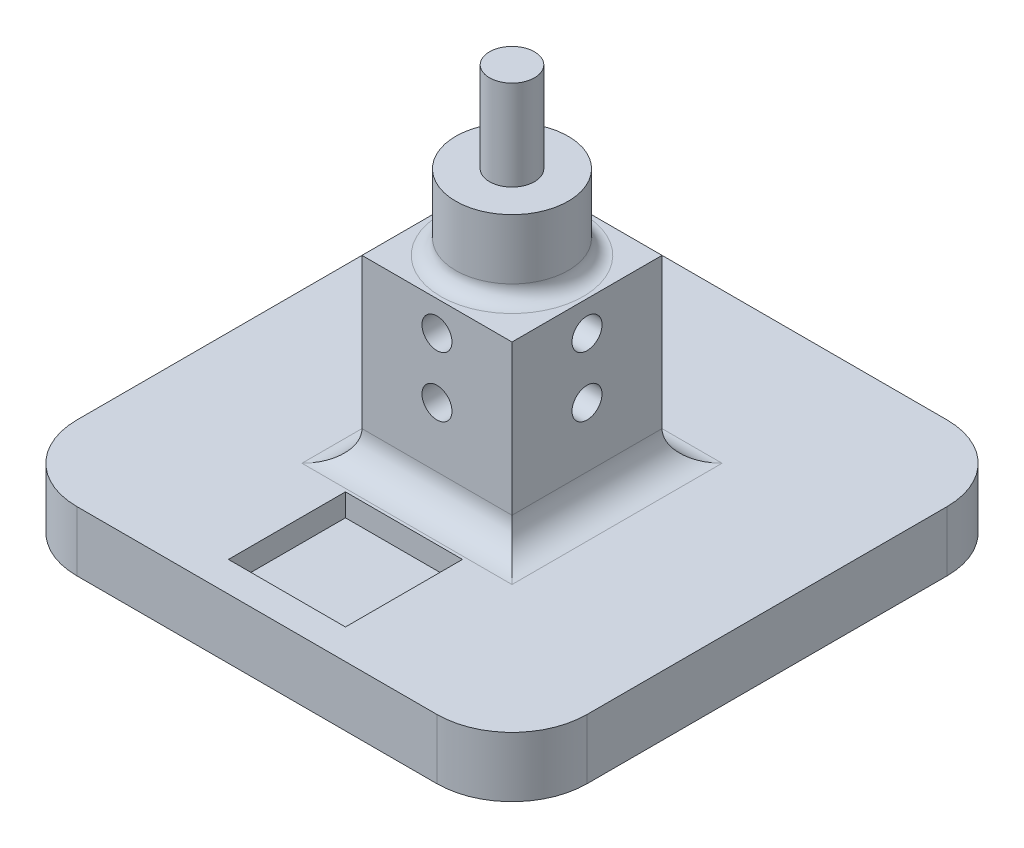
SolidWorks part; units mm, degrees
ref_plane "前视基准面" through (0, 0, 0) normal (0, 0, 1) x (1, 0, 0)
ref_plane "上视基准面" through (0, 0, 0) normal (0, 1, 0) x (1, 0, 0)
ref_plane "右视基准面" through (0, 0, 0) normal (1, 0, 0) x (0, 0, -1)
other "Configuration Table"
sketch "草图1" plane through (0, 0, 0) normal (0, 1, 0) x (1, 0, 0)
  circle A0 centre (0, 0) radius 7.5
  dimension "D1" = 15
extrude "凸台-拉伸1" add sketch "草图1" along normal blind 10
sketch "草图2" plane through (0, 0, 0) normal (0, -1, 0) x (1, 0, 0)
  line L1 (-10, -10) -> (10, -10)
  line L2 (-10, -10) -> (-10, 10)
  line L3 (-10, 10) -> (10, 10)
  line L4 (10, -10) -> (10, 10)
  line L5 (-10, -10) -> (10, 10) construction
  line L6 (-10, 10) -> (10, -10) construction
  point P0 (0, 0)
  dimension "D1" = 20
  dimension "D2" = 20
extrude "凸台-拉伸2" add sketch "草图2" along normal blind 24
sketch "草图3" plane through (0, -24, 0) normal (0, -1, 0) x (1, 0, 0)
  line L1 (-34, -34) -> (34, -34)
  line L2 (-34, -34) -> (-34, 34)
  line L3 (-34, 34) -> (34, 34)
  line L4 (34, -34) -> (34, 34)
  line L5 (-34, -34) -> (34, 34) construction
  line L6 (-34, 34) -> (34, -34) construction
  point P0 (0, 0)
  dimension "D1" = 68
  dimension "D2" = 68
extrude "凸台-拉伸3" add sketch "草图3" along normal blind 8
fillet "圆角1" radius 10 4 edges at (-34, -28, 34) (-34, -28, -34) (34, -28, -34) (34, -28, 34)
sketch "草图4" plane through (10, 0, 0) normal (1, 0, 0) x (0, 0, -1)
  circle A0 centre (0, -4) radius 2
  circle A1 centre (0, -12) radius 2
  point P4 (0, 0)
  dimension "D3" = 4
  dimension "D4" = 4
  dimension "D1" = 4
  dimension "D2" = 8
extrude "切除-拉伸1" cut sketch "草图4" against normal blind 23
pattern_circular "阵列(圆周)1" count 2 every 90 about axis through (0, 10, 0) along (0, -1, 0) of "切除-拉伸1"
sketch "草图5" plane through (0, -32, 0) normal (0, -1, 0) x (1, 0, 0)
  circle A0 centre (0, 0) radius 5
  dimension "D1" = 10
extrude "切除-拉伸2" cut sketch "草图5" against normal blind 31
sketch "草图6" plane through (0, -24, 0) normal (0, 1, 0) x (1, 0, 0)
  line L0 (24, -34) -> (-24, -34) construction
  line L1 (-7.8, -14.4) -> (7.8, -14.4)
  line L2 (-7.8, -14.4) -> (-7.8, -30)
  line L3 (-7.8, -30) -> (7.8, -30)
  line L4 (7.8, -14.4) -> (7.8, -30)
  point P4 (0, -14.4)
  dimension "D1" = 15.6
  dimension "D2" = 15.6
  dimension "D3" = 4
fillet "圆角3" radius 4 4 edges at (-10, -24, 0) (0, -24, -10) (10, -24, 0) (0, -24, 10)
extrude "切除-拉伸3" cut sketch "草图6" against normal blind 3
sketch "草图7" plane through (0, 10, 0) normal (0, 1, 0) x (1, 0, 0)
  circle A0 centre (0, 0) radius 3
  dimension "D1" = 6
extrude "凸台-拉伸4" add sketch "草图7" along normal blind 12
fillet "圆角4" radius 2 1 edges at (0, 0, 7.5)
